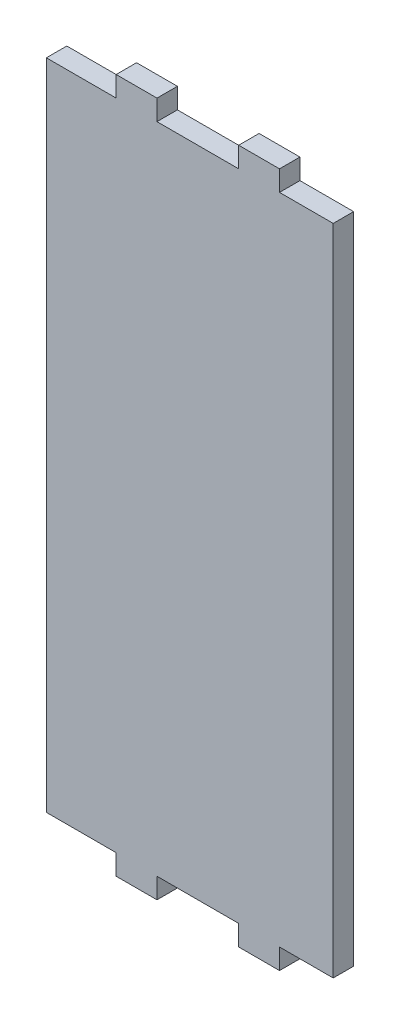
SolidWorks part; units mm, degrees
ref_plane "Front Plane" through (0, 0, 0) normal (0, 0, 1) x (1, 0, 0)
ref_plane "Top Plane" through (0, 0, 0) normal (0, 1, 0) x (1, 0, 0)
ref_plane "Right Plane" through (0, 0, 0) normal (1, 0, 0) x (0, 0, -1)
sketch "Sketch1" plane through (0, 0, 0) normal (0, 0, 1) x (1, 0, 0)
  line L2 (-176.4767, 160) -> (-176.4767, 0)
  line L4 (-149.395, 165) -> (-159.395, 165) construction
  line L5 (-159.395, 165) -> (-159.395, 160) construction
  line L7 (-149.395, 160) -> (-149.395, 165) construction
  line L8 (-119.395, 165) -> (-129.395, 165) construction
  line L9 (-129.395, 165) -> (-129.395, 160) construction
  line L21 (-129.395, 0) -> (-129.395, -5) construction
  line L22 (-129.395, -5) -> (-119.395, -5) construction
  line L25 (-159.395, 0) -> (-159.395, -5) construction
  line L26 (-159.395, -5) -> (-149.395, -5) construction
  line L27 (-149.395, -5) -> (-149.395, 0) construction
  line L36 (-149.395, 165) -> (-159.395, 165)
  line L37 (-159.395, 165) -> (-159.395, 160)
  line L39 (-149.395, 160) -> (-149.395, 165)
  line L40 (-119.395, 165) -> (-129.395, 165)
  line L41 (-129.395, 165) -> (-129.395, 160)
  line L43 (-119.395, 160) -> (-119.395, 165)
  line L53 (-129.395, 0) -> (-129.395, -5)
  line L54 (-129.395, -5) -> (-119.395, -5)
  line L55 (-119.395, -5) -> (-119.395, 0)
  line L57 (-159.395, 0) -> (-159.395, -5)
  line L58 (-159.395, -5) -> (-149.395, -5)
  line L59 (-149.395, -5) -> (-149.395, 0)
  line L65 (-189.395, 0) -> (-189.395, 160) construction
  line L66 (-176.4767, 0) -> (-159.395, 0)
  line L67 (-149.395, 0) -> (-129.395, 0)
  line L68 (-119.395, 0) -> (-106.2499, 0)
  line L69 (-106.2499, 160) -> (-119.395, 160)
  line L70 (-149.395, 160) -> (-129.395, 160)
  line L71 (-176.4767, 160) -> (-159.395, 160)
  line L72 (-106.2499, 160) -> (-106.2499, 0)
extrude "Boss-Extrude1" add sketch "Sketch1" along normal blind 5
